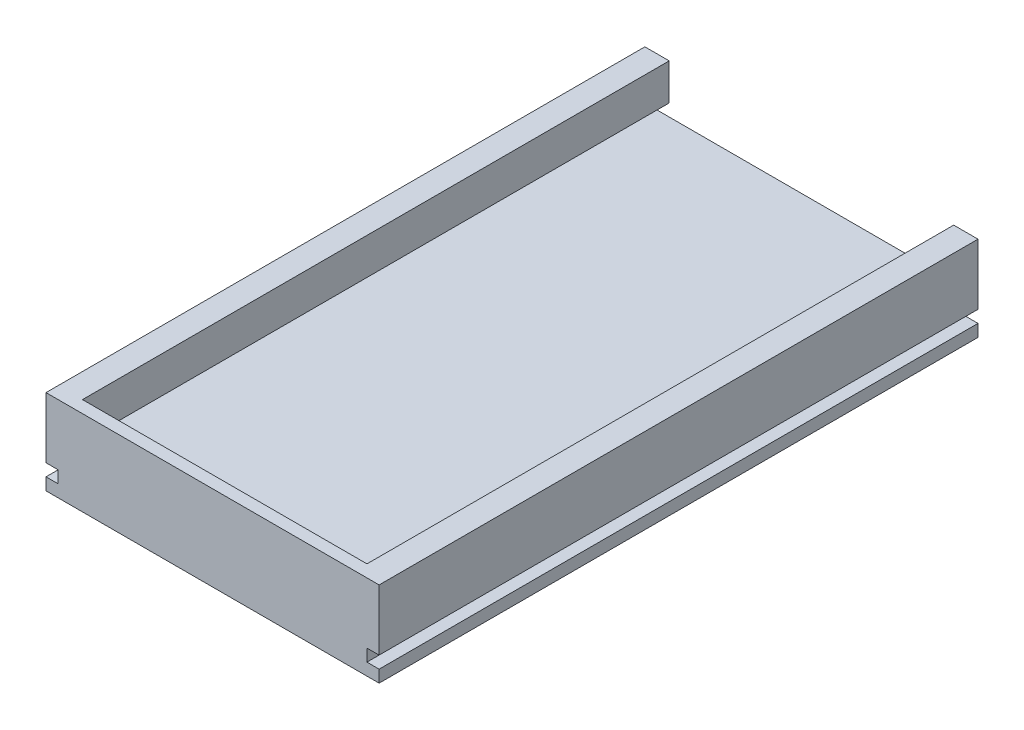
SolidWorks part; units mm, degrees
material "ABS"
ref_plane "Alzado" through (0, 0, 0) normal (0, 0, 1) x (1, 0, 0)
ref_plane "Planta" through (0, 0, 0) normal (0, 1, 0) x (1, 0, 0)
ref_plane "Vista lateral" through (0, 0, 0) normal (1, 0, 0) x (0, 0, -1)
sketch "Croquis11" plane through (0, 0, 0) normal (0, 1, 0) x (1, 0, 0)
  line L1 (-13.7, 24.63) -> (13.7, 24.63)
  line L2 (-13.7, 24.63) -> (-13.7, -24.63)
  line L3 (-13.7, -24.63) -> (13.7, -24.63)
  line L4 (13.7, 24.63) -> (13.7, -24.63)
  line L5 (-13.7, 24.63) -> (13.7, -24.63) construction
  line L6 (-13.7, -24.63) -> (13.7, 24.63) construction
  point P0 (0, 0)
  dimension "D1" = 49.26
  dimension "D2" = 27.4
extrude "Saliente-Extruir3" add sketch "Croquis11" along normal blind 3
sketch "Croquis21" plane through (0, 0, -24.63) normal (0, 0, -1) x (-1, 0, 0)
  line L0 (-13.7, 3) -> (-13.7, 0) construction
  line L1 (-13.7, 2) -> (-12.7, 2)
  line L2 (-13.7, 2) -> (-13.7, 1)
  line L3 (-13.7, 1) -> (-12.7, 1)
  line L4 (-12.7, 2) -> (-12.7, 1)
  line L5 (-12.7, 1.5) -> (-12.195, 1.5)
  line L6 (-13.7, 1.5) -> (-14.4392, 1.5)
  line L7 (0, 3) -> (0, 1.2209)
  line L8 (-13.7, 3) -> (13.7, 3) construction
  line L9 (13.7, 1.5) -> (14.4392, 1.5)
  line L10 (12.7, 1.5) -> (12.195, 1.5)
  line L11 (12.7, 2) -> (12.7, 1)
  line L12 (13.7, 1) -> (12.7, 1)
  line L13 (13.7, 2) -> (13.7, 1)
  line L14 (13.7, 2) -> (12.7, 2)
  line M2 (13.7, 0) -> (13.7, 3)
  line M4 (-13.7, 3) -> (-13.7, 0)
  dimension "D1" = 1
  dimension "D2" = 0
  dimension "D3" = 1
extrude "Cortar-Extruir1" cut sketch "Croquis21" against normal blind 56 contours L4 L1 L2 L3 M4 | L14 L11 L12 M2
sketch "Croquis23" plane through (0, 0, 24.63) normal (0, 0, 1) x (1, 0, 0)
  line L0 (-13.7, 3) -> (-13.7, 5)
  line L1 (-13.7, 5) -> (-11.7, 5)
  line L2 (-11.7, 5) -> (-11.7, 4)
  line L3 (-11.7, 4) -> (-12.7, 4)
  line L4 (-12.7, 4) -> (-12.7, 3)
  line L5 (-13.7, 3) -> (13.7, 3) construction
  line L6 (0, 3) -> (0, 5.5853)
  line L7 (12.7, 4) -> (12.7, 3)
  line L8 (11.7, 4) -> (12.7, 4)
  line L9 (11.7, 5) -> (11.7, 4)
  line L10 (13.7, 5) -> (11.7, 5)
  line L11 (13.7, 3) -> (13.7, 5)
  line L12 (-13.7, 3) -> (-12.7, 3)
  line L13 (12.7, 3) -> (13.7, 3)
  line M9 (13.7, 3) -> (-13.7, 3)
  dimension "D1" = 2
  dimension "D2" = 1
extrude "Saliente-Extruir4" add sketch "Croquis23" against normal blind 49.26 contours L4 L3 L2 L1 L0 M9 | L11 L10 L9 L8 L7 M9
sketch "Croquis24" plane through (0, 3, 0) normal (0, 1, 0) x (1, 0, 0)
  line L5 (0, 0) -> (-4.7052, 0)
  line L6 (13.7, -24.63) -> (13.7, -23.63)
  line L7 (-13.7, -23.63) -> (13.7, -23.63)
  line L8 (-13.7, -24.63) -> (-13.7, -23.63)
  line L9 (-13.7, -24.63) -> (13.7, -24.63)
  line M1 (12.7, -24.63) -> (12.7, 24.63)
  line M3 (-12.7, 24.63) -> (-12.7, -24.63)
  line M4 (-12.7, -24.63) -> (12.7, -24.63)
extrude "Saliente-Extruir6" add sketch "Croquis24" along normal blind 2 contours L7 M3 M4 M1
sketch "Croquis26" plane through (0, 5, 0) normal (0, 1, 0) x (1, 0, 0)
  line L0 (-13.7, 24.63) -> (-11.7, 24.63)
  line L1 (-11.7, 24.63) -> (-11.7, -23.63)
  line L2 (-11.7, -23.63) -> (11.7, -23.63)
  line L3 (11.7, -23.63) -> (11.7, 24.63)
  line L4 (11.7, 24.63) -> (13.7, 24.63)
  line L5 (13.7, 24.63) -> (13.7, -24.63)
  line L6 (13.7, -24.63) -> (-13.7, -24.63)
  line L7 (-13.7, -24.63) -> (-13.7, 24.63)
extrude "Saliente-Extruir7" add sketch "Croquis26" along normal blind 2
